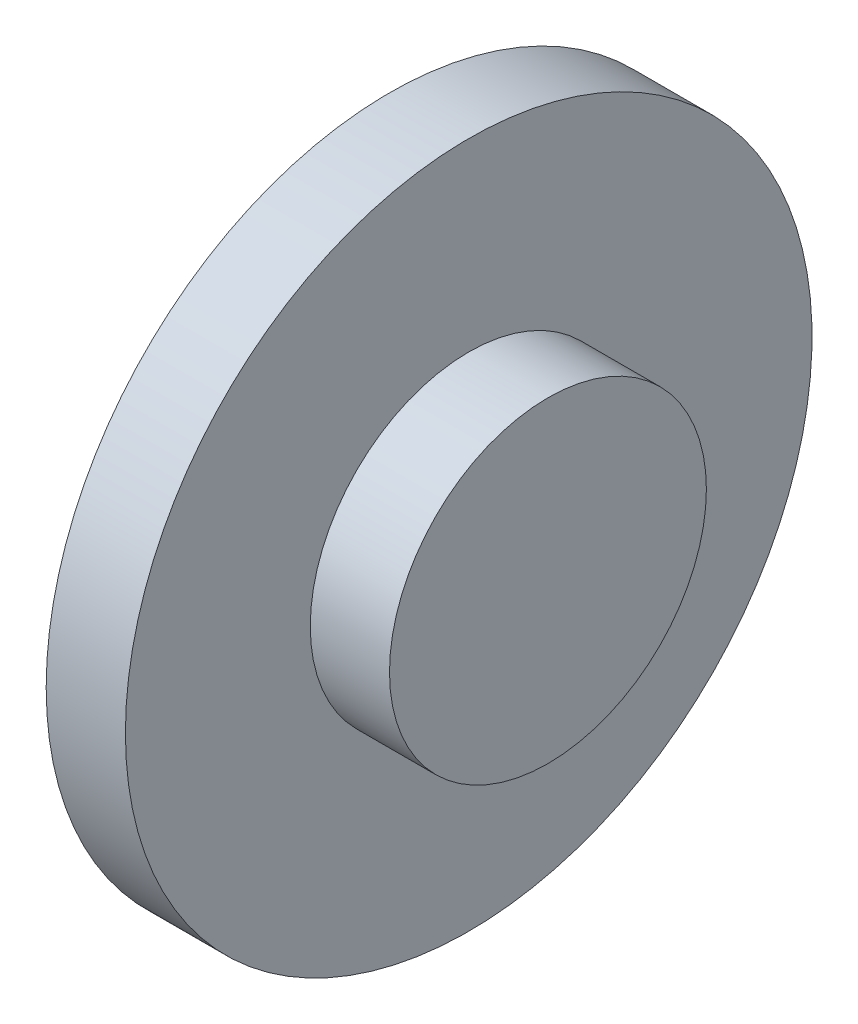
SolidWorks part; units mm, degrees
ref_plane "Спереди" through (0, 0, 0) normal (0, 0, 1) x (1, 0, 0)
ref_plane "Сверху" through (0, 0, 0) normal (0, 1, 0) x (1, 0, 0)
ref_plane "Справа" through (0, 0, 0) normal (1, 0, 0) x (0, 0, -1)
sketch "Эскиз1" plane through (0, 0, 0) normal (0, 0, 1) x (1, 0, 0)
  line L0 (0, 0) -> (14.5661, 0) construction
  line L1 (0, 0) -> (0, 13)
  line L2 (0, 13) -> (3, 13)
  line L3 (3, 13) -> (3, 6)
  line L4 (3, 6) -> (6, 6)
  line L5 (6, 6) -> (6, 0)
  line L6 (6, 0) -> (0, 0)
  dimension "D1" = 26
  dimension "D2" = 3
  dimension "D3" = 6
  dimension "D4" = 12
revolve "Повернуть1" add sketch "Эскиз1" angle 360 about L0
